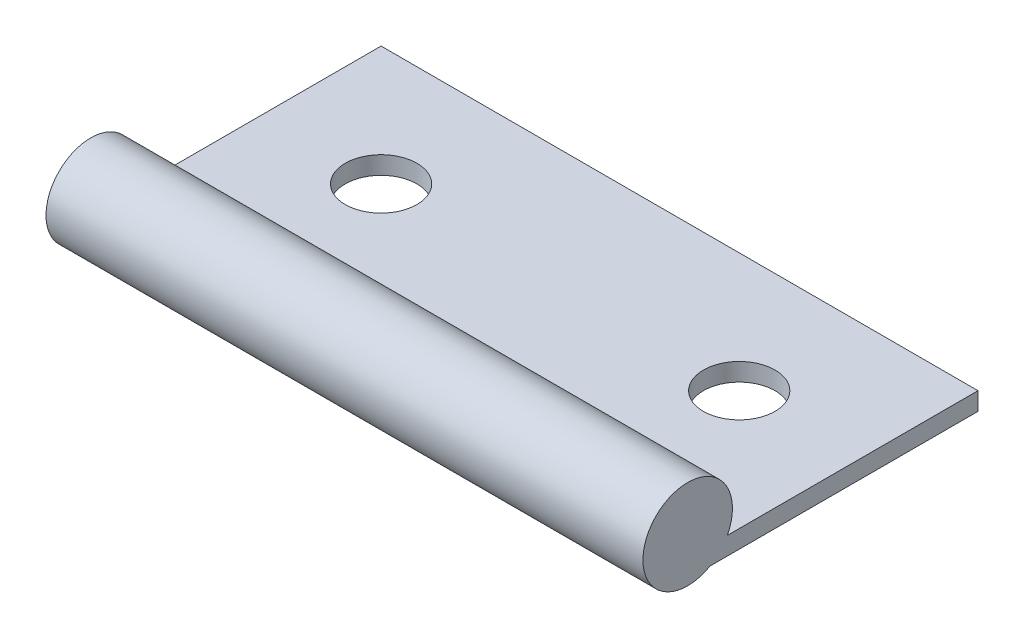
SolidWorks part; units mm, degrees
ref_plane "Alzado" through (0, 0, 0) normal (0, 0, 1) x (1, 0, 0)
ref_plane "Planta" through (0, 0, 0) normal (0, 1, 0) x (1, 0, 0)
ref_plane "Vista lateral" through (0, 0, 0) normal (1, 0, 0) x (0, 0, -1)
sketch "Croquis1" plane through (0, 0, 0) normal (1, 0, 0) x (0, 0, -1)
  line L0 (0, -3.75) -> (7.1526, -3.75) construction
  line L1 (1.8708, -3.25) -> (24.3166, -3.25)
  line L3 (3.3166, -1.75) -> (24.3166, -1.75)
  line L4 (24.3166, -3.25) -> (24.3166, -1.75)
  arc A0 (3.3166, -1.75) -> (1.8708, -3.25) centre (0, 0) ccw
  point P0 (0, 0)
  point P7 (-2.9178, 3.25)
  dimension "D1" = 7.5
  dimension "D2" = 21
  dimension "D3" = 1
  dimension "D4" = 1.5
extrude "Saliente-Extruir1" add sketch "Croquis1" along normal blind 50
sketch "Croquis2" plane through (0, -1.75, 0) normal (0, 1, 0) x (1, 0, 0)
  line L0 (0, 14.3166) -> (10, 14.3166) construction
  line L1 (0, 24.3166) -> (0, 3.3166) construction
  line L2 (10, 14.3166) -> (40, 14.3166) construction
  line L3 (40, 14.3166) -> (50, 14.3166) construction
  line L4 (50, 24.3166) -> (50, 3.3166) construction
  line L5 (25, 14.3166) -> (25, 24.3166) construction
  line L6 (50, 24.3166) -> (0, 24.3166) construction
  circle A0 centre (10, 14.3166) radius 3
  circle A1 centre (40, 14.3166) radius 3
  dimension "D1" = 6
  dimension "D2" = 30
  dimension "D3" = 10
extrude "Cortar-Extruir1" cut sketch "Croquis2" against normal blind 50
